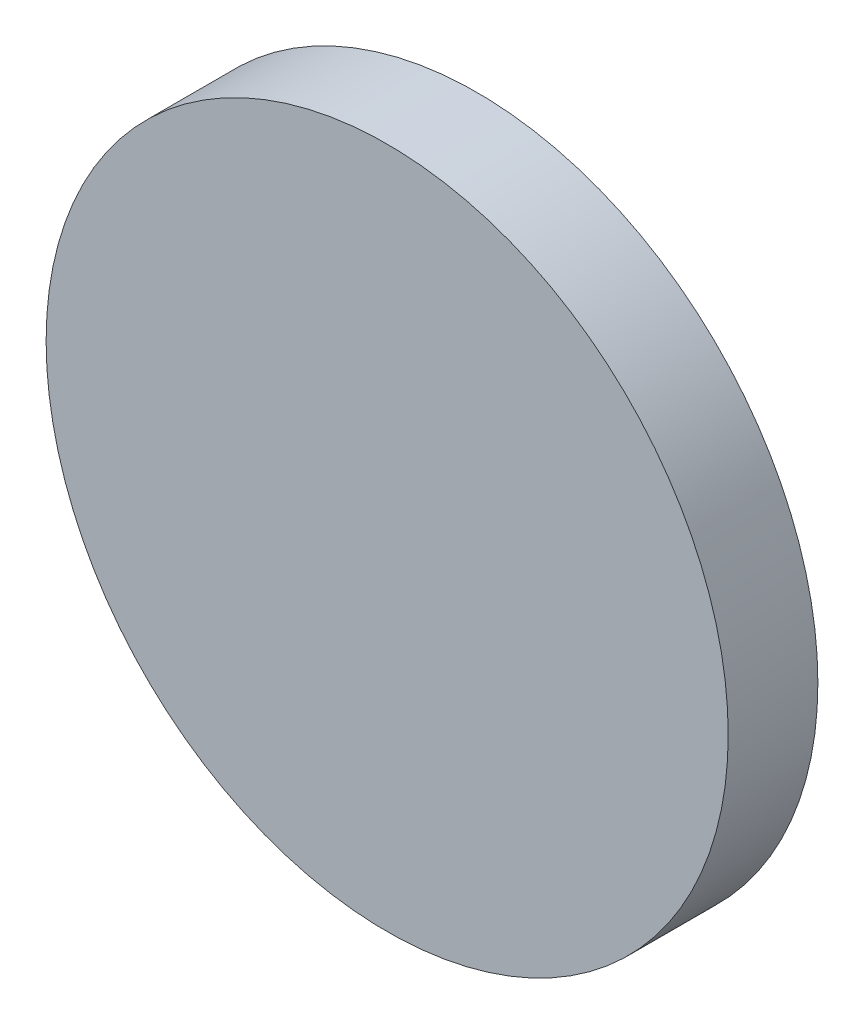
SolidWorks part; units mm, degrees
ref_plane "Front Plane" through (0, 0, 0) normal (0, 0, 1) x (1, 0, 0)
ref_plane "Top Plane" through (0, 0, 0) normal (0, 1, 0) x (1, 0, 0)
ref_plane "Right Plane" through (0, 0, 0) normal (1, 0, 0) x (0, 0, -1)
sketch "Sketch1" plane through (0, 0, 0) normal (0, 0, 1) x (1, 0, 0)
  circle A2 centre (0, 0) radius 12.0777
extrude "Boss-Extrude1" add sketch "Sketch1" along normal blind 3.175
